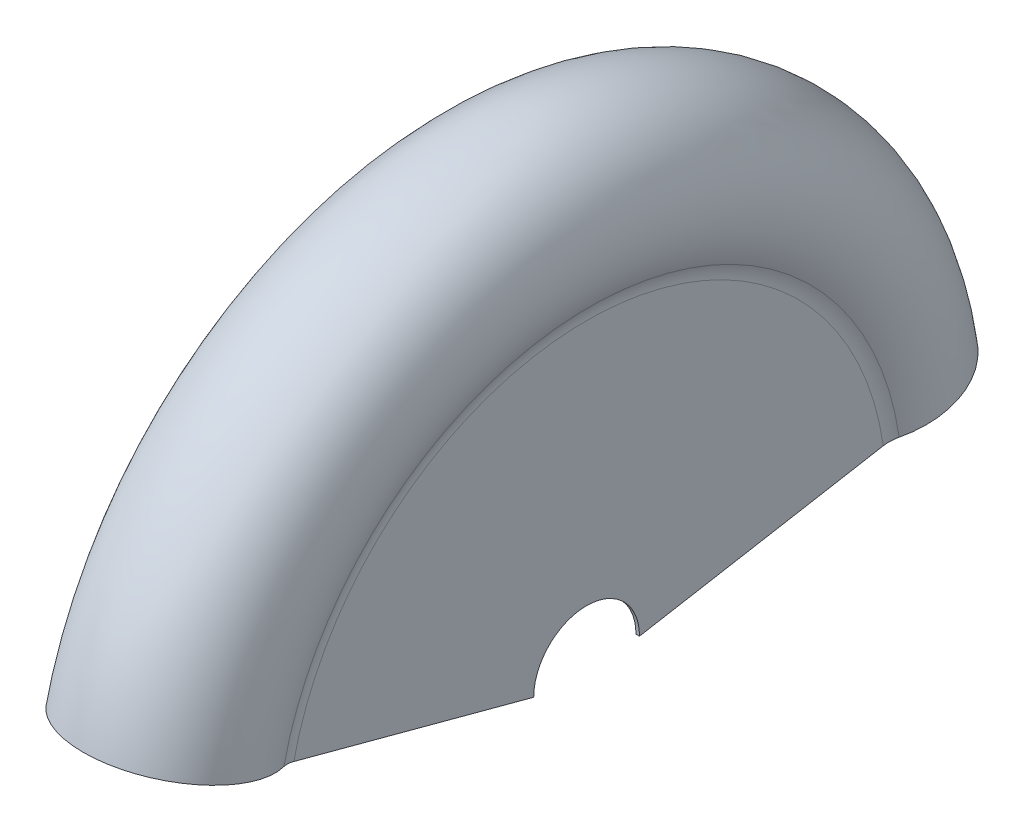
SolidWorks part; units mm, degrees
ref_plane "Спереди" through (0, 0, 0) normal (0, 0, 1) x (1, 0, 0)
ref_plane "Сверху" through (0, 0, 0) normal (0, 1, 0) x (1, 0, 0)
ref_plane "Справа" through (0, 0, 0) normal (1, 0, 0) x (0, 0, -1)
other "Configuration Table"
sketch "Sketch1" plane through (0, 0, 0) normal (0, 0, 1) x (1, 0, 0)
  line L0 (0, 82.8653) -> (0, -65.42) construction
  line L1 (-44, 0) -> (44, 0)
  line L2 (44, 0) -> (44, 170)
  line L3 (-44, 170) -> (-44, 0)
  arc A1 (45.6098, 177.5122) -> (-45.6098, 177.5122) centre (0, 198) ccw
  arc A2 (44, 170) -> (45.6098, 177.5122) centre (62.3333, 170) cw
  arc A3 (-44, 170) -> (-45.6098, 177.5122) centre (-62.3333, 170) ccw
  point P7 (44, 163.7951)
  dimension "D2" = 50
  dimension "D5" = 198
  dimension "D3" = 170
  dimension "D1" = 88
revolve "Revolve1" add sketch "Sketch1" angle 360 about L1
sketch "Sketch2" plane through (0, 0, 0) normal (1, 0, 0) x (0, 0, -1)
  line L0 (-289.3355, 69.4887) -> (-30, 0)
  line L1 (30, 0) -> (310.6645, 49.4887)
  line L2 (310.6645, 49.4887) -> (310.6645, -330.5113)
  line L3 (310.6645, -330.5113) -> (-289.3355, -330.5113)
  line L4 (-289.3355, -330.5113) -> (-289.3355, 69.4887)
  line L5 (-70.8176, 0) -> (61.1534, 0) construction
  circle A0 centre (0, 0) radius 30
  point P12 (-70.8176, 0)
  point P13 (0, 0)
  dimension "D1" = 60
  dimension "D2" = 15
  dimension "D3" = 10
  dimension "D4" = 600
  dimension "D5" = 400
  dimension "D6" = 380
extrude "Cut-Extrude1" cut sketch "Sketch2" against normal through all both and the other way through all
shell "Shell1" thickness 2
